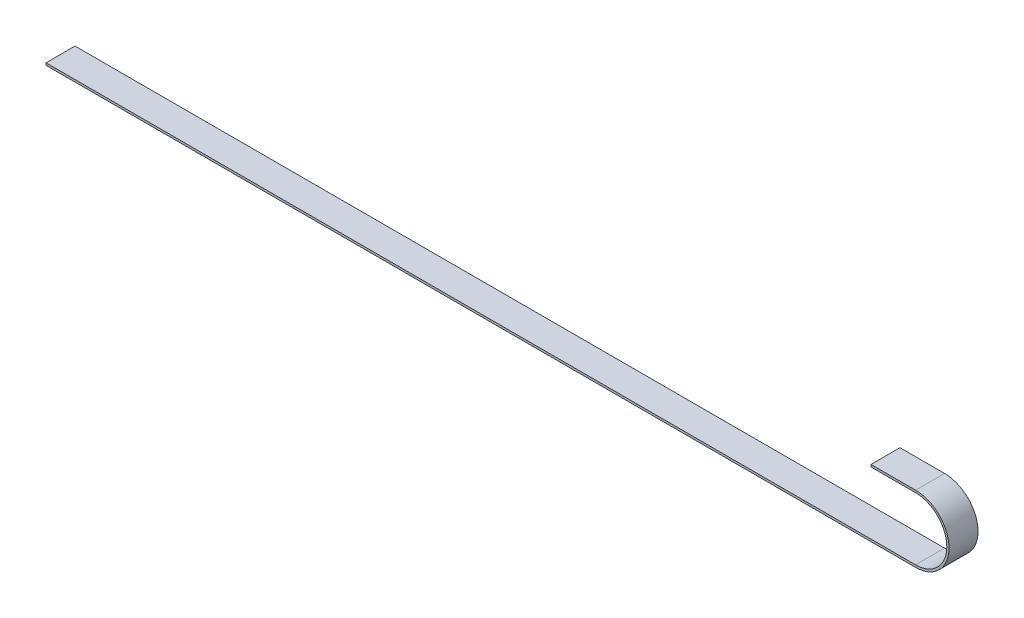
SolidWorks part; units mm, degrees
ref_plane "Front Plane" through (0, 0, 0) normal (0, 0, 1) x (1, 0, 0)
ref_plane "Top Plane" through (0, 0, 0) normal (0, 1, 0) x (1, 0, 0)
ref_plane "Right Plane" through (0, 0, 0) normal (1, 0, 0) x (0, 0, -1)
sketch "Sketch1" plane through (0, 0, 0) normal (0, 0, 1) x (1, 0, 0)
  line L0 (0, 0) -> (390, 0)
  line L1 (390, 30) -> (370, 30)
  arc A0 (390, 0) -> (390, 30) centre (390, 15) ccw
  dimension "D1" = 30
  dimension "D2" = 390
  dimension "D3" = 20
extrude "Extrude-Thin1" add sketch "Sketch1" along normal mid plane 13 thin thin type one direction reverse wall 1
